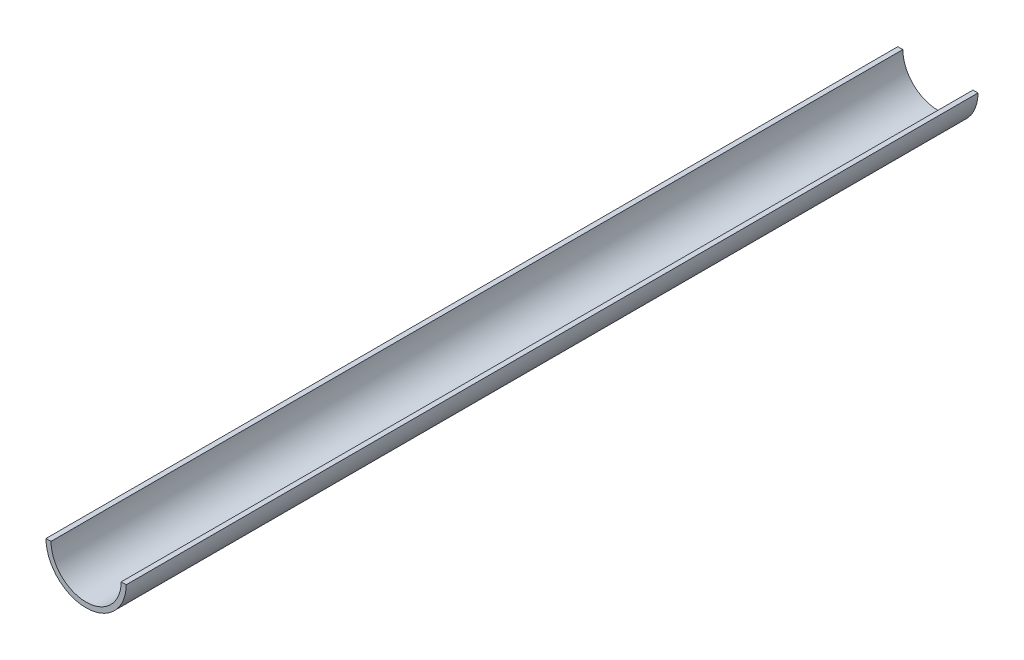
SolidWorks part; units mm, degrees
material "Acrylic (Medium-high impact)"
ref_plane "Front Plane" through (0, 0, 0) normal (0, 0, 1) x (1, 0, 0)
ref_plane "Top Plane" through (0, 0, 0) normal (0, 1, 0) x (1, 0, 0)
ref_plane "Right Plane" through (0, 0, 0) normal (1, 0, 0) x (0, 0, -1)
sketch "Sketch1" plane through (0, 0, 0) normal (0, 0, 1) x (1, 0, 0)
  circle A0 centre (0, 0) radius 25.4
  circle A1 centre (0, 0) radius 22.225
  dimension "D1" = 50.8
  dimension "D2" = 44.45
extrude "Boss-Extrude1" add sketch "Sketch1" along normal blind 914.4
sketch "Sketch2" plane through (0, 0, 0) normal (0, 0, -1) x (-1, 0, 0)
  circle A0 centre (0, 0) radius 25.4 construction
  circle A1 centre (0, 0) radius 25.4
extrude "Cut-Extrude1" cut sketch "Sketch2" against normal through all from offset 539.75 offset against normal yes
sketch "Sketch4" plane through (0, 0, 0) normal (0, 0, 1) x (1, 0, 0)
  line L0 (-25.4, 0) -> (25.4, 0)
  circle A0 centre (0, 0) radius 25.4 construction
  arc A1 (25.4, 0) -> (-25.4, 0) centre (0, 0) ccw
extrude "Cut-Extrude3" cut sketch "Sketch4" along normal through all
ref_plane "Plane1" through (0, -25.4, 0) normal (0, -1, 0) x (-1, 0, 0)
ref_plane "Plane3" through (0, -22.225, 0) normal (0, 1, 0) x (1, 0, 0)
ref_plane "Plane2" through (0, 0, 15.875) normal (0, 0, -1) x (-1, 0, 0)
